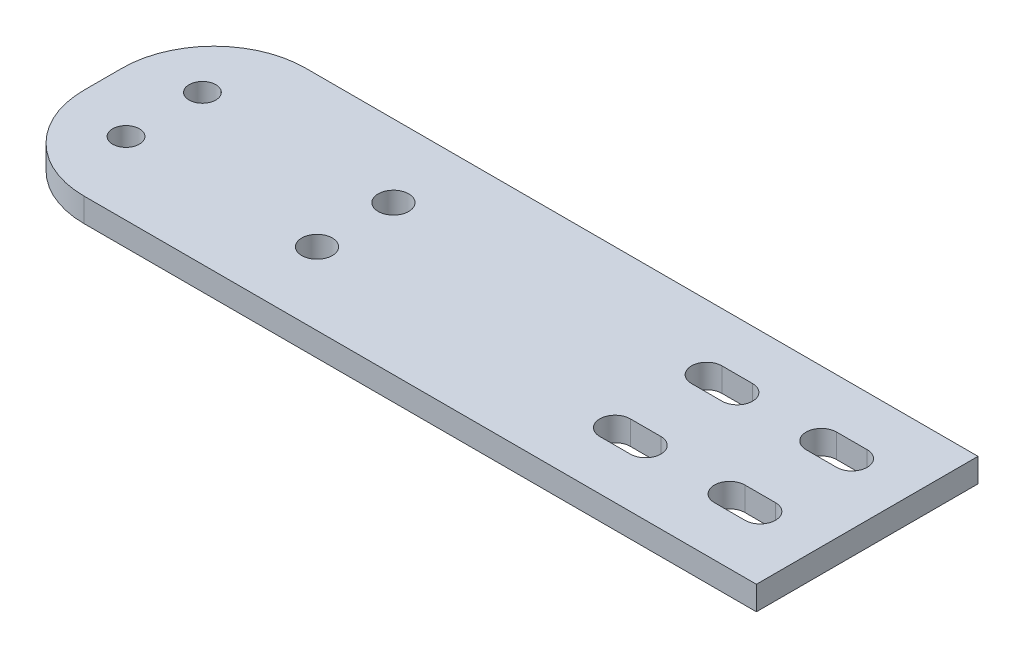
SolidWorks part; units mm, degrees
ref_plane "Front Plane" through (0, 0, 0) normal (0, 0, 1) x (1, 0, 0)
ref_plane "Top Plane" through (0, 0, 0) normal (0, 1, 0) x (1, 0, 0)
ref_plane "Right Plane" through (0, 0, 0) normal (1, 0, 0) x (0, 0, -1)
sketch "Sketch1" plane through (0, 0, 0) normal (0, 1, 0) x (1, 0, 0)
  line L1 (0, 29) -> (200, 29)
  line L2 (0, 29) -> (0, -29)
  line L3 (0, -29) -> (200, -29)
  line L4 (200, 29) -> (200, -29)
  point P4 (0, 0)
  dimension "D1" = 58
  dimension "D2" = 200
extrude "Boss-Extrude1" add sketch "Sketch1" along normal blind 6.25
sketch "Sketch2" plane through (0, 0, 0) normal (0, 1, 0) x (1, 0, 0)
  line L0 (176, 12) -> (184, 12) construction
  line L1 (176, 16) -> (184, 16)
  line L2 (176, 8) -> (184, 8)
  line L3 (200, -29) -> (200, 29) construction
  line L4 (146, 12) -> (154, 12) construction
  line L5 (146, 16) -> (154, 16)
  line L6 (146, 8) -> (154, 8)
  line L7 (146, -12) -> (154, -12) construction
  line L8 (146, -8) -> (154, -8)
  line L9 (146, -16) -> (154, -16)
  line L10 (176, -12) -> (184, -12) construction
  line L11 (176, -8) -> (184, -8)
  line L12 (176, -16) -> (184, -16)
  circle A0 centre (16, 10) radius 3.5
  circle A1 centre (16, -10) radius 3.5
  arc A2 (176, 16) -> (176, 8) centre (176, 12) ccw
  arc A3 (184, 8) -> (184, 16) centre (184, 12) ccw
  arc A4 (146, 16) -> (146, 8) centre (146, 12) ccw
  arc A5 (154, 8) -> (154, 16) centre (154, 12) ccw
  arc A6 (146, -8) -> (146, -16) centre (146, -12) ccw
  arc A7 (154, -16) -> (154, -8) centre (154, -12) ccw
  arc A8 (176, -8) -> (176, -16) centre (176, -12) ccw
  arc A9 (184, -16) -> (184, -8) centre (184, -12) ccw
  point P4 (180, 12)
  point P17 (150, 12)
  point P24 (150, -12)
  point P31 (180, -12)
  dimension "D2" = 7
  dimension "D5" = 4
  dimension "D1" = 16
  dimension "D3" = 20
  dimension "D4" = 10
  dimension "D6" = 12
  dimension "D7" = 8
  dimension "D8" = 20
  dimension "D11" = 30
  dimension "D12" = 24
  dimension "D9" = 2
  dimension "D10" = 2
extrude "Cut-Extrude1" cut sketch "Sketch2" along normal through all
fillet "Fillet1" radius 24 2 edges at (0, 3.125, -29) (0, 3.125, 29)
sketch "Sketch3" plane through (0, 0, 0) normal (0, 1, 0) x (1, 0, 0)
  circle A0 centre (66, -10) radius 4
  circle A1 centre (66, 10) radius 4
  dimension "D4" = 8
  dimension "D1" = 20
  dimension "D2" = 10
  dimension "D3" = 66
extrude "Cut-Extrude2" cut sketch "Sketch3" along normal blind 10
equation "\"D4@Sketch2\"=\"D3@Sketch2\"/2"
